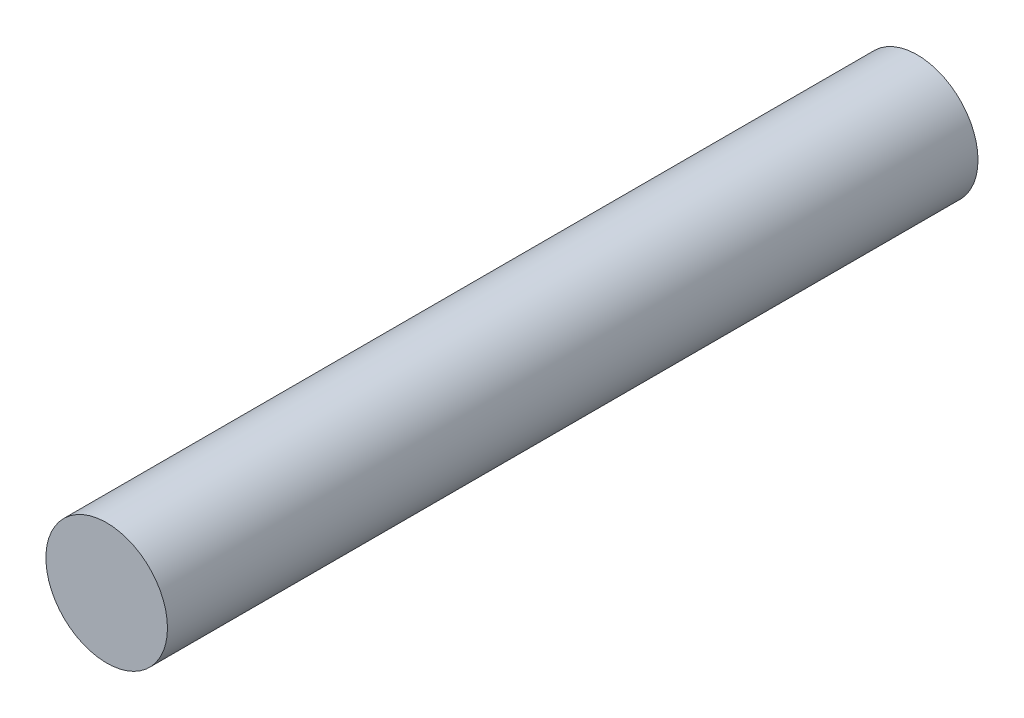
SolidWorks part; units mm, degrees
material "PETG"
ref_plane "Front Plane" through (0, 0, 0) normal (0, 0, 1) x (1, 0, 0)
ref_plane "Top Plane" through (0, 0, 0) normal (0, 1, 0) x (1, 0, 0)
ref_plane "Right Plane" through (0, 0, 0) normal (1, 0, 0) x (0, 0, -1)
sketch "Sketch1" plane through (0, 0, 0) normal (0, 0, 1) x (1, 0, 0)
  circle A0 centre (0, 0) radius 1.5
  dimension "D1" = 3
extrude "Boss-Extrude1" add sketch "Sketch1" along normal blind 20
ref_plane "Plane1" through (0, 0, 10) normal (0, 0, 1) x (1, 0, 0)
